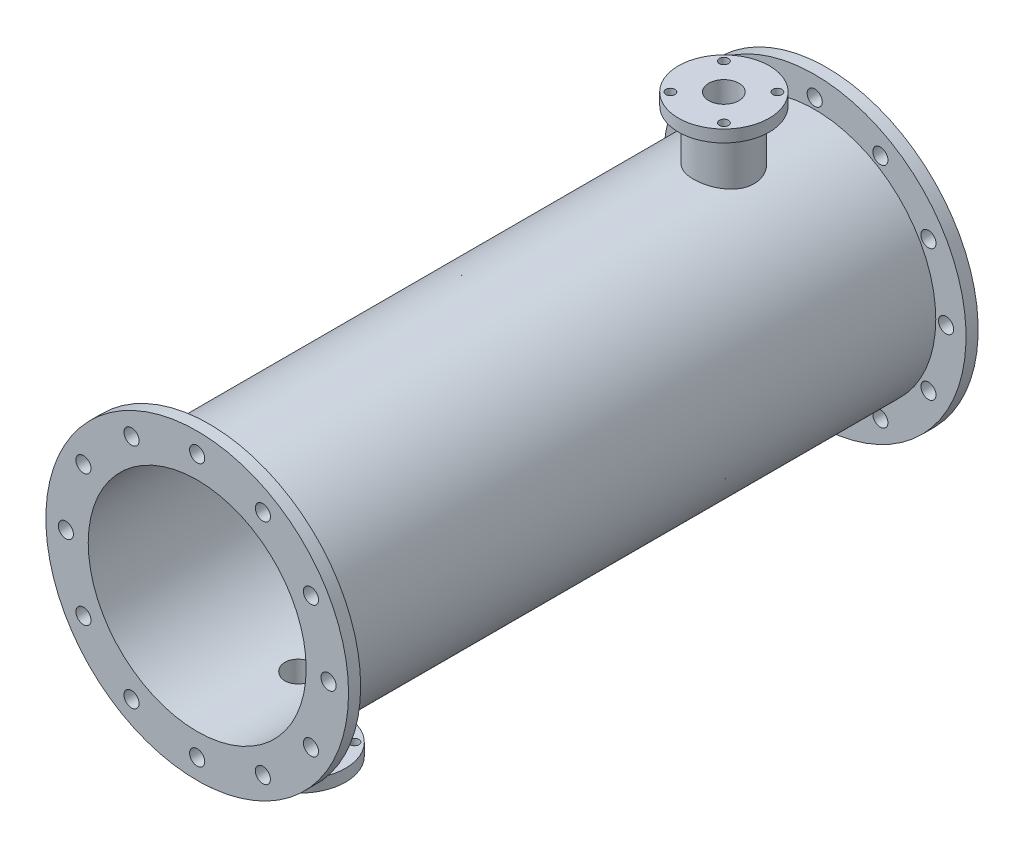
SolidWorks part; units mm, degrees
ref_plane "Front Plane" through (0, 0, 0) normal (0, 0, 1) x (1, 0, 0)
ref_plane "Top Plane" through (0, 0, 0) normal (0, 1, 0) x (1, 0, 0)
ref_plane "Right Plane" through (0, 0, 0) normal (1, 0, 0) x (0, 0, -1)
sketch "Sketch1" plane through (0, 0, 0) normal (0, 0, 1) x (1, 0, 0)
  circle A0 centre (0, 0) radius 200
  circle A1 centre (0, 0) radius 180
extrude "Boss-Extrude1" add sketch "Sketch1" along normal blind 1000
ref_plane "Plane3" through (0, 0, 150) normal (0, 0, 1) x (1, 0, 0)
sketch "Sketch6" plane through (0, 0, 150) normal (0, 0, 1) x (1, 0, 0)
  line L0 (0, 0) -> (0, 200) construction
  line L1 (0, 200) -> (-25, 200) construction
  line L2 (-50, 200) -> (-50, 280) construction
  line L3 (-50, 280) -> (-75, 280) construction
  line L4 (-75, 280) -> (-75, 300) construction
  line L5 (-75, 300) -> (-25, 300) construction
  line L6 (-25, 300) -> (-25, 200) construction
  line L7 (-50, 200) -> (-50, 193.6492)
  line L8 (-25, 200) -> (-25, 197.9519)
  line L9 (-25, 197.9519) -> (-25, 300)
  line L10 (-25, 300) -> (-75, 300)
  line L11 (-75, 300) -> (-75, 280)
  line L12 (-75, 280) -> (-50, 280)
  line L13 (-50, 280) -> (-50, 193.6492)
  line L14 (-50, 193.6492) -> (-25, 197.9519)
  circle A0 centre (0, 0) radius 200 construction
revolve "Revolve1" add sketch "Sketch6" angle 360 about L0
sketch "Sketch7" plane through (0, 300, 0) normal (0, 1, 0) x (1, 0, 0)
  circle A0 centre (0, -150) radius 25
extrude "Cut-Extrude1" cut sketch "Sketch7" against normal blind 150
ref_plane "Plane4" through (0, 0, 850) normal (0, 0, 1) x (1, 0, 0)
sketch "Sketch8" plane through (0, 0, 850) normal (0, 0, 1) x (1, 0, 0)
  line L0 (0, 0) -> (0, -200) construction
  line L1 (0, -200) -> (50, -200) construction
  line L2 (25, -200) -> (25, -300) construction
  line L3 (25, -300) -> (75, -300) construction
  line L4 (75, -300) -> (75, -280) construction
  line L5 (75, -280) -> (50, -280) construction
  line L6 (50, -280) -> (50, -200) construction
  line L7 (25, -200) -> (25, -198.4313)
  line L9 (50, -200) -> (50, -192.5731)
  line L10 (50, -192.5731) -> (25, -198.4313)
  line L11 (25, -200) -> (25, -300)
  line L12 (25, -300) -> (75, -300)
  line L13 (75, -300) -> (75, -280)
  line L14 (75, -280) -> (50, -280)
  line L15 (50, -280) -> (50, -200)
  circle A0 centre (0, 0) radius 200 construction
revolve "Revolve2" add sketch "Sketch8" angle 360 about L0
sketch "Sketch9" plane through (0, -300, 0) normal (0, -1, 0) x (1, 0, 0)
  circle A0 centre (0, 850) radius 25
extrude "Cut-Extrude2" cut sketch "Sketch9" against normal blind 150
sketch "Sketch10" plane through (0, 300, 0) normal (0, 1, 0) x (1, 0, 0)
  line L0 (38.9022, -111.0978) -> (0, -150) construction
  line L2 (49.5088, -100.4912) -> (38.9022, -111.0978) construction
  line L3 (38.9022, -111.0978) -> (49.5088, -100.4912) construction
  circle A0 centre (44.2055, -105.7945) radius 7.5
  circle A1 centre (44.2055, -194.2055) radius 7.5
  circle A2 centre (-44.2055, -194.2055) radius 7.5
  circle A3 centre (-44.2055, -105.7945) radius 7.5
  point P15 (0, -150)
  dimension "D1" = 4
extrude "Cut-Extrude3" cut sketch "Sketch10" against normal blind 50
sketch "Sketch11" plane through (0, -300, 0) normal (0, -1, 0) x (1, 0, 0)
  line L0 (39.6001, 889.6001) -> (50.2067, 900.2067) construction
  line L3 (50.2067, 900.2067) -> (39.6001, 889.6001) construction
  line L4 (0, 850) -> (44.9034, 894.9034) construction
  circle A1 centre (44.9034, 894.9034) radius 7.5
  circle A2 centre (44.9034, 805.0966) radius 7.5
  circle A3 centre (-44.9034, 805.0966) radius 7.5
  circle A4 centre (-44.9034, 894.9034) radius 7.5
  point P15 (0, 850)
  dimension "D1" = 4
extrude "Cut-Extrude4" cut sketch "Sketch11" against normal blind 50
sketch "Sketch12" plane through (0, 0, 1000) normal (0, 0, 1) x (1, 0, 0)
  line L0 (0, 250) -> (0, 229.4566) construction
  line L1 (0, 229.4566) -> (0, 204.4566) construction
  circle A0 centre (0, 0) radius 180
  circle A1 centre (0, 0) radius 250
  circle A2 centre (0, 216.9566) radius 12.5
  circle A3 centre (108.4783, 187.89) radius 12.5
  circle A4 centre (187.89, 108.4783) radius 12.5
  circle A5 centre (216.9566, 0) radius 12.5
  circle A6 centre (187.89, -108.4783) radius 12.5
  circle A7 centre (108.4783, -187.89) radius 12.5
  circle A8 centre (0, -216.9566) radius 12.5
  circle A9 centre (-108.4783, -187.89) radius 12.5
  circle A10 centre (-187.89, -108.4783) radius 12.5
  circle A11 centre (-216.9566, 0) radius 12.5
  circle A12 centre (-187.89, 108.4783) radius 12.5
  circle A13 centre (-108.4783, 187.89) radius 12.5
  point P33 (0, 0)
  dimension "D1" = 12
extrude "Boss-Extrude3" add sketch "Sketch12" along normal blind 20
sketch "Sketch13" plane through (0, 0, 0) normal (0, 0, -1) x (-1, 0, 0)
  circle A0 centre (0, 0) radius 180
  circle A1 centre (0, 0) radius 250
  circle A2 centre (216.9566, 0) radius 12.5
  circle A3 centre (187.89, -108.4783) radius 12.5
  circle A4 centre (108.4783, -187.89) radius 12.5
  circle A5 centre (0, -216.9566) radius 12.5
  circle A6 centre (-108.4783, -187.89) radius 12.5
  circle A7 centre (-187.89, -108.4783) radius 12.5
  circle A8 centre (-216.9566, 0) radius 12.5
  circle A9 centre (-187.89, 108.4783) radius 12.5
  circle A10 centre (-108.4783, 187.89) radius 12.5
  circle A11 centre (0, 216.9566) radius 12.5
  circle A12 centre (108.4783, 187.89) radius 12.5
  circle A13 centre (187.89, 108.4783) radius 12.5
  point P31 (0, 0)
  dimension "D1" = 12
extrude "Boss-Extrude4" add sketch "Sketch13" along normal blind 20
